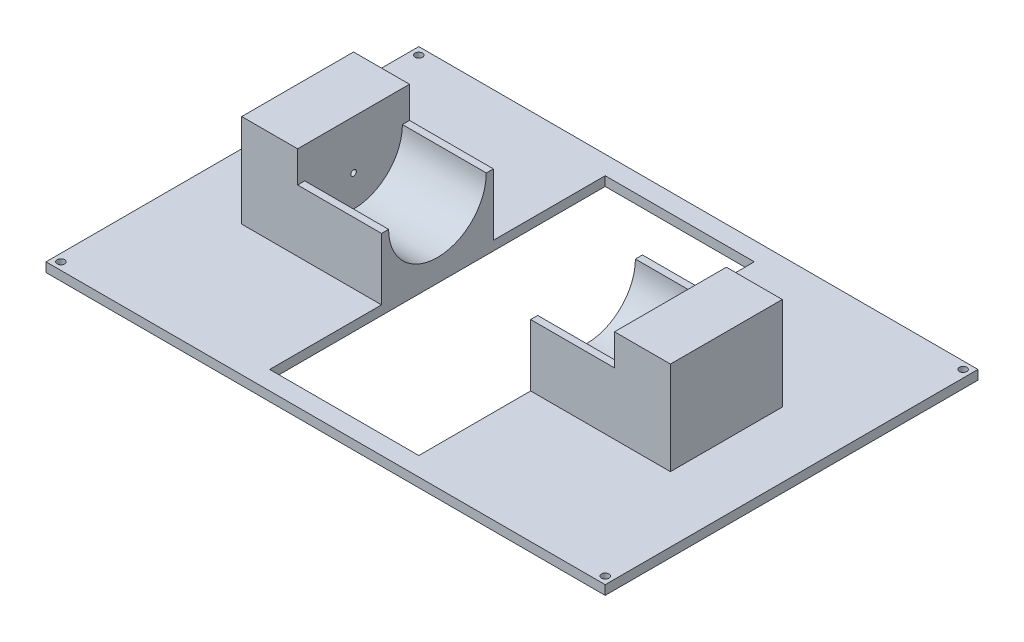
SolidWorks part; units mm, degrees
ref_plane "Front Plane" through (0, 0, 0) normal (0, 0, 1) x (1, 0, 0)
ref_plane "Top Plane" through (0, 0, 0) normal (0, 1, 0) x (1, 0, 0)
ref_plane "Right Plane" through (0, 0, 0) normal (1, 0, 0) x (0, 0, -1)
sketch "Sketch1" plane through (0, 0, 0) normal (0, 1, 0) x (1, 0, 0)
  line L0 (0, 0) -> (0, 23.4539) construction
  line L1 (-150, -100) -> (150, -100)
  line L2 (-150, -100) -> (-150, 100)
  line L3 (-150, 100) -> (150, 100)
  line L4 (150, -100) -> (150, 100)
  line L5 (-150, -100) -> (150, 100) construction
  line L6 (-150, 100) -> (150, -100) construction
  line L7 (0, 0) -> (-15.0246, 0) construction
  circle A0 centre (-146, 96) radius 2
  circle A1 centre (146, 96) radius 2
  circle A2 centre (146, -96) radius 2
  circle A3 centre (-146, -96) radius 2
  point P0 (0, 0)
  dimension "D2" = 4
  dimension "D1" = 300
  dimension "200" = 200
  dimension "D3" = 4
  dimension "D4" = 4
extrude "Boss-Extrude1" add sketch "Sketch1" along normal blind 5
sketch "Sketch3" plane through (0, 5, 0) normal (0, 1, 0) x (1, 0, 0)
  line L1 (40, -90) -> (-40, -90)
  line L2 (40, -90) -> (40, 90)
  line L3 (40, 90) -> (-40, 90)
  line L4 (-40, -90) -> (-40, 90)
  line L5 (40, -90) -> (-40, 90) construction
  line L6 (40, 90) -> (-40, -90) construction
  point P0 (0, 0)
  dimension "D1" = 180
  dimension "D2" = 80
extrude "Cut-Extrude1" cut sketch "Sketch3" against normal up to next
sketch "Sketch4" plane through (0, 5, 0) normal (0, 1, 0) x (1, 0, 0)
  line L0 (-150, 100) -> (-150, -100) construction
  line L1 (-85, -30) -> (-115, -30)
  line L2 (-85, -30) -> (-85, 30)
  line L3 (-85, 30) -> (-115, 30)
  line L4 (-115, -30) -> (-115, 30)
  line L5 (-85, -30) -> (-115, 30) construction
  line L6 (-85, 30) -> (-115, -30) construction
  point P0 (-100, 0)
  point P5 (0, 0)
  point P7 (-78.6954, 0)
  dimension "D1" = 30
  dimension "D2" = 60
  dimension "D3" = 50
extrude "Boss-Extrude2" add sketch "Sketch4" along normal blind 50
sketch "Sketch5" plane through (-85, 0, 0) normal (1, 0, 0) x (0, 0, -1)
  line L0 (-26.2, 38.1919) -> (-30, 38.1919)
  line L1 (-30, 55) -> (-30, 5) construction
  line L2 (-30, 38.1919) -> (-30, 5)
  line L3 (-30, 5) -> (30, 5)
  line L4 (30, 5) -> (30, 38.1919)
  line L5 (30, 55) -> (30, 5) construction
  line L6 (30, 38.1919) -> (26.2, 38.1919)
  arc A0 (-26.2, 38.1919) -> (26.2, 38.1919) centre (0, 38.1919) ccw
  dimension "D1" = 26.2
extrude "Boss-Extrude3" add sketch "Sketch5" along normal blind 45
sketch "Sketch7" plane through (-85, 0, 0) normal (1, 0, 0) x (0, 0, -1)
  circle A0 centre (0, 28.7651) radius 1.5
  dimension "D1" = 3
extrude "Cut-Extrude2" cut sketch "Sketch7" against normal blind 5
mirror "Mirror3" about plane through (0, 0, 0) normal (1, 0, 0) of "Boss-Extrude3", "Cut-Extrude2", "Boss-Extrude2"
